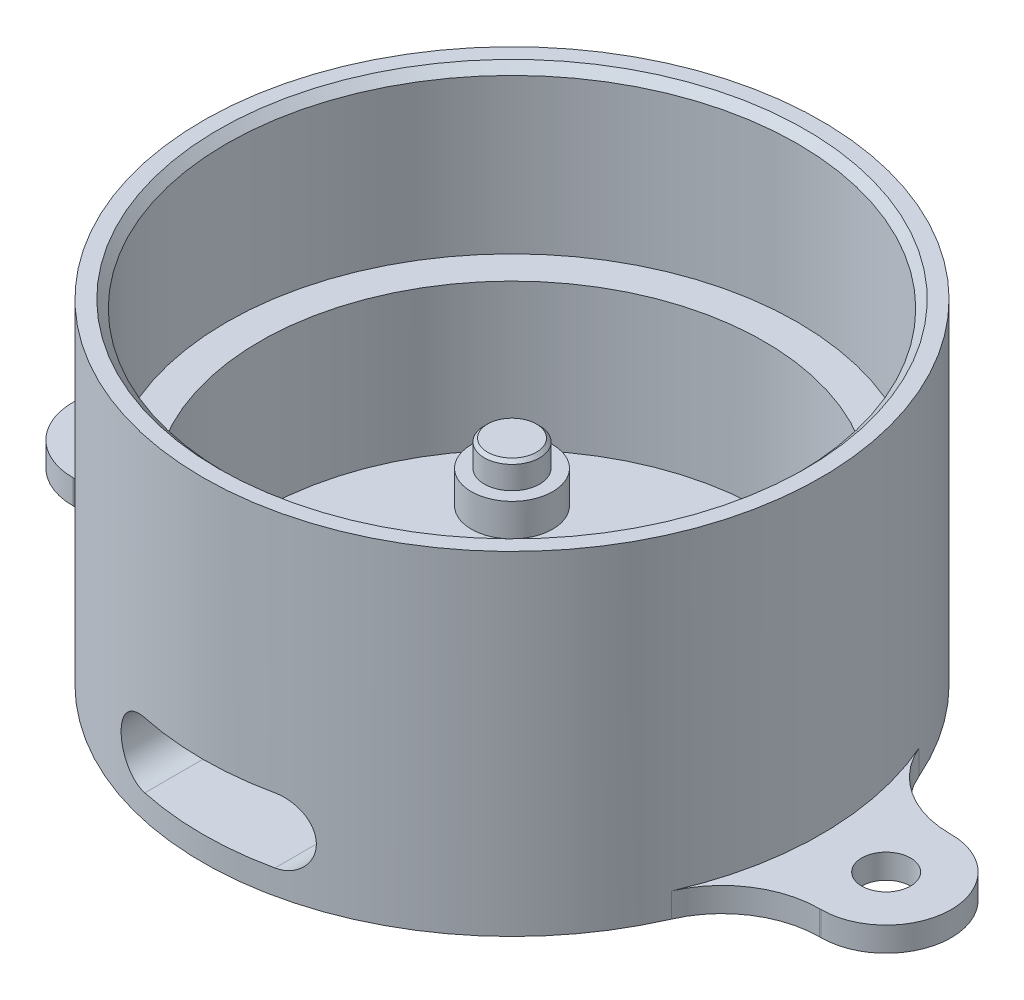
SolidWorks part; units mm, degrees
ref_plane "Спереди" through (0, 0, 0) normal (0, 0, 1) x (1, 0, 0)
ref_plane "Сверху" through (0, 0, 0) normal (0, 1, 0) x (1, 0, 0)
ref_plane "Справа" through (0, 0, 0) normal (1, 0, 0) x (0, 0, -1)
sketch "Эскиз2" plane through (0, 0, 0) normal (0, 1, 0) x (1, 0, 0)
  line L0 (-39.1892, 0) -> (35.8981, 0) construction
  line L1 (0, 30.0612) -> (0, -35.5892) construction
  line L2 (-23, 4) -> (-22.9129, 4)
  line L3 (-23, -4) -> (-22.9129, -4)
  line L4 (23, -4) -> (22.9129, -4)
  line L5 (23, 4) -> (22.9129, 4)
  arc A0 (-17.4138, -7.6) -> (17.4138, -7.6) centre (0, 0) ccw
  circle A1 centre (-23, 0) radius 1.5
  arc A2 (-23, 4) -> (-23, -4) centre (-23, 0) ccw
  arc A3 (23, 4) -> (23, -4) centre (23, 0) cw
  circle A4 centre (23, 0) radius 1.5
  arc A5 (17.4138, 7.6) -> (-17.4138, 7.6) centre (0, 0) ccw
  arc A6 (17.4138, -7.6) -> (22.9129, -4) centre (22.9129, -10) cw
  arc A7 (17.4138, 7.6) -> (22.9129, 4) centre (22.9129, 10) ccw
  arc A8 (-17.4138, 7.6) -> (-22.9129, 4) centre (-22.9129, 10) cw
  arc A9 (-17.4138, -7.6) -> (-22.9129, -4) centre (-22.9129, -10) ccw
  point P20 (18.5742, -4)
  point P23 (18.5742, 4)
  point P26 (-18.5742, 4)
  point P29 (-18.5742, -4)
  dimension "D1" = 38
  dimension "D2" = 8
  dimension "D3" = 3
  dimension "D5" = 6
  dimension "D4" = 23
extrude "Бобышка-Вытянуть2" add sketch "Эскиз2" along normal blind 1.5
sketch "Эскиз3" plane through (0, 1.5, 0) normal (0, 1, 0) x (1, 0, 0)
  circle A0 centre (0, 0) radius 15.5
  circle A1 centre (0, 0) radius 19 construction
  circle A2 centre (0, 0) radius 19
  point P0 (0, 0)
  dimension "D2" = 31
extrude "Бобышка-Вытянуть3" add sketch "Эскиз3" along normal blind 9
sketch "Эскиз4" plane through (0, 1.5, 0) normal (0, 1, 0) x (1, 0, 0)
  line L1 (-8, 8) -> (8, 8) construction
  line L2 (-8, 8) -> (-8, -8) construction
  line L3 (-8, -8) -> (8, -8) construction
  line L4 (8, 8) -> (8, -8) construction
  line L5 (-8, 8) -> (8, -8) construction
  line L6 (-8, -8) -> (8, 8) construction
  circle A0 centre (-8, -8) radius 2.5
  circle A1 centre (8, -8) radius 2.5
  circle A2 centre (8, 8) radius 2.5
  circle A3 centre (-8, 8) radius 2.5
  point P0 (0, 0)
  dimension "D2" = 5
  dimension "D1" = 16
extrude "Бобышка-Вытянуть4" add sketch "Эскиз4" along normal blind 2
sketch "Эскиз8" plane through (0, 10.5, 0) normal (0, 1, 0) x (1, 0, 0)
  circle A0 centre (0, 0) radius 17.55
  circle A1 centre (0, 0) radius 19 construction
  circle A2 centre (0, 0) radius 19
  dimension "D1" = 35.1
extrude "Бобышка-Вытянуть5" add sketch "Эскиз8" along normal blind 10
sketch "Эскиз9" plane through (0, 3.5, 0) normal (0, 1, 0) x (1, 0, 0)
  circle A2 centre (-8, 8) radius 1.7
  circle A3 centre (-8, 8) radius 1.7
  circle A5 centre (8, 8) radius 1.6
  circle A6 centre (8, 8) radius 1.6
  circle A8 centre (-8, -8) radius 1.6
  circle A9 centre (-8, -8) radius 1.6
  circle A11 centre (8, -8) radius 1.6
  circle A12 centre (8, -8) radius 1.6
  dimension "D1" = 0.8
  dimension "D2" = 0.9
  dimension "D3" = 0.9
  dimension "D4" = 0.9
extrude "Бобышка-Вытянуть6" add sketch "Эскиз9" along normal blind 1.6
ref_plane "Плоскость1" through (0, 0, 20) normal (0, 0, 1) x (1, 0, 0)
sketch "Эскиз11" plane through (0, 0, 20) normal (0, 0, 1) x (1, 0, 0)
  line L0 (0, -1.0852) -> (0, 26.3725) construction
  line L1 (-4, 3.5) -> (4, 3.5) construction
  line L2 (-4, 5.5) -> (4, 5.5)
  line L3 (-4, 1.5) -> (4, 1.5)
  arc A0 (-4, 5.5) -> (-4, 1.5) centre (-4, 3.5) ccw
  arc A1 (4, 1.5) -> (4, 5.5) centre (4, 3.5) ccw
  point P5 (0, 3.5)
  point P10 (0, 1.5)
  dimension "D2" = 2
  dimension "D1" = 1.5
  dimension "D3" = 8
extrude "Вырез-Вытянуть2" cut sketch "Эскиз11" against normal up to next
chamfer "Фаска1" distance 0.5 angle 45 1 edges at (0, 20.5, 17.55)
chamfer "Фаска2" distance 0.2 angle 45 4 edges at (8, 5.1, 9.6) (-8, 5.1, 9.6) (8, 5.1, -6.4) (-8, 5.1, -6.3)
